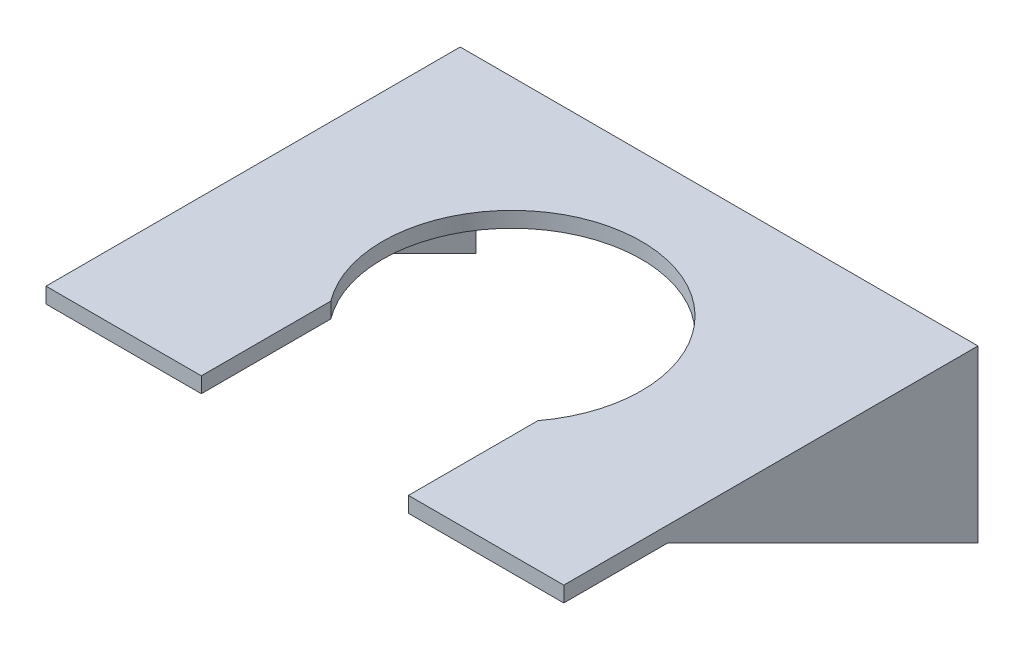
SolidWorks part; units mm, degrees
ref_plane "Front Plane" through (0, 0, 0) normal (0, 0, 1) x (1, 0, 0)
ref_plane "Top Plane" through (0, 0, 0) normal (0, 1, 0) x (1, 0, 0)
ref_plane "Right Plane" through (0, 0, 0) normal (1, 0, 0) x (0, 0, -1)
sketch "Sketch1" plane through (0, 0, 0) normal (0, 0, 1) x (1, 0, 0)
  line L1 (-25, -1.0618) -> (25, -1.0618)
  line L2 (-25, -1.0618) -> (-25, -2.5618)
  line L3 (-25, -2.5618) -> (25, -2.5618)
  line L4 (25, -1.0618) -> (25, -2.5618)
  point P6 (0, -1.0618)
  dimension "D1" = 1.5
  dimension "D3" = 50
extrude "Boss-Extrude1" add sketch "Sketch1" along normal blind 40
sketch "Sketch2" plane through (0, -1.0618, 0) normal (0, 1, 0) x (1, 0, 0)
  line L0 (-25, -20) -> (25, -20) construction
  line L1 (-25, -40) -> (-25, 0) construction
  line L2 (25, -40) -> (25, 0) construction
  line L3 (-10, -27.5) -> (-10, -40)
  line L5 (10, -27.5) -> (10, -40)
  line L6 (25, 0) -> (-25, 0) construction
  line L7 (-10, -40) -> (10, -40)
  arc A0 (10, -27.5) -> (-10, -27.5) centre (0, -20) ccw
  dimension "D2" = 25
  dimension "D1" = 20
  dimension "D3" = 10
  dimension "D4" = 10
extrude "Cut-Extrude1" cut sketch "Sketch2" against normal up to surface (1.5 mm away) up to face at (0, -2.5618, 20)
ref_plane "Plane4" through (-20, 0, 0) normal (-1, 0, 0) x (0, 0, 1)
sketch "Sketch4" plane through (-25, 0, 0) normal (-1, 0, 0) x (0, 0, 1)
  line L0 (0, -2.5618) -> (0, -17.5618)
  line L1 (0, -17.5618) -> (30, -2.5618)
  line L2 (40, -2.5618) -> (0, -2.5618) construction
  line L3 (30, -2.5618) -> (0, -2.5618)
  dimension "D1" = 15
  dimension "D2" = 30
extrude "Boss-Extrude2" add sketch "Sketch4" against normal blind 1.5
mirror "Mirror1" about plane through (0, 0, 0) normal (1, 0, 0) of "Boss-Extrude2"
